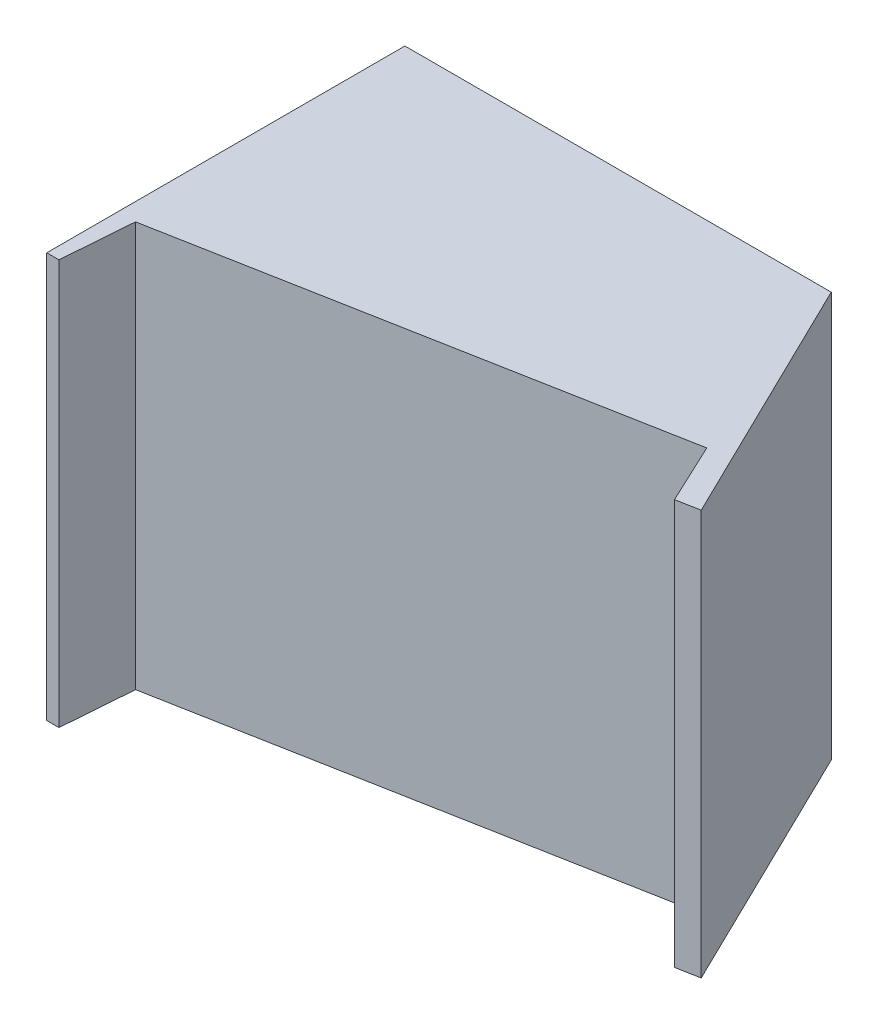
SolidWorks part; units mm, degrees
ref_plane "Front Plane" through (0, 0, 0) normal (0, 0, 1) x (1, 0, 0)
ref_plane "Top Plane" through (0, 0, 0) normal (0, 1, 0) x (1, 0, 0)
ref_plane "Right Plane" through (0, 0, 0) normal (1, 0, 0) x (0, 0, -1)
other "Graphic1"
other "Graphic (Closed) -1"
sketch "Sketch1" plane through (0, 0, 0) normal (0, 0, 1) x (1, 0, 0)
  line L1 (0, 0) -> (449.9783, 0)
  line L2 (0, 0) -> (0, 427.5737)
  line L3 (0, 427.5737) -> (449.9783, 427.5737)
  line L4 (449.9783, 0) -> (449.9783, 427.5737)
  dimension "D1" = 427.5737
  dimension "D2" = 449.9783
extrude "Boss-Extrude1" add sketch "Sketch1" along normal blind 378
draft "Draft2" type of draft neutral plane draft angle 26 faces to draft 1 face at (449.9783, 213.7869, 189) neutral plane through (0, 0, 0) neutral plane normal (0, 0, -1) parameters "D1"=26
sketch "Sketch2" plane through (0, 427.5737, 0) normal (0, 1, 0) x (1, 0, 0)
  line L0 (12.8564, -378) -> (18.6039, -302.8778)
  line L1 (18.6039, -302.8778) -> (526.6673, -208.0604)
  line L2 (526.6673, -208.0604) -> (556.8544, -272.3551)
  line L3 (556.8544, -272.3551) -> (580.6489, -267.9144)
  line L4 (634.3413, -378) -> (0, -378) construction
  line L5 (634.3413, -378) -> (449.9783, 0) construction
  line L6 (0, -378) -> (0, 0) construction
  line L7 (449.9783, 0) -> (0, 0) construction
  dimension "D1" = 12.8564
  dimension "D2" = 18.6039
  dimension "D3" = 526.6673
  dimension "D4" = 556.8544
  dimension "D5" = 580.6489
  dimension "D6" = 208.0604
  dimension "D7" = 272.3551
extrude "Cut-Extrude1" cut sketch "Sketch2" against normal through all and the other way through all flip side to cut
